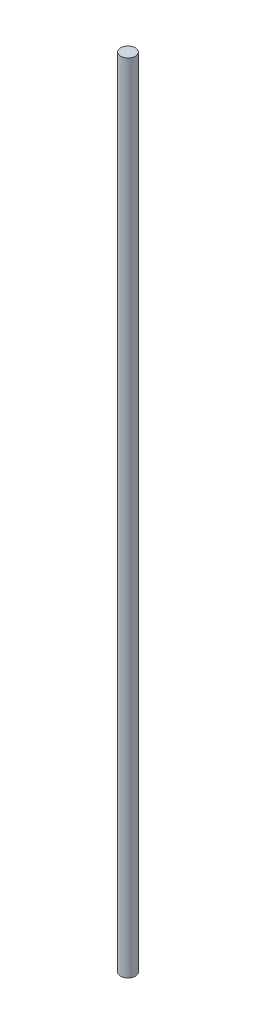
SolidWorks part; units mm, degrees
ref_plane "Plan de face" through (0, 0, 0) normal (0, 0, 1) x (1, 0, 0)
ref_plane "Plan de dessus" through (0, 0, 0) normal (0, 1, 0) x (1, 0, 0)
ref_plane "Plan de droite" through (0, 0, 0) normal (1, 0, 0) x (0, 0, -1)
sketch "Esquisse1" plane through (0, 0, 0) normal (0, 1, 0) x (1, 0, 0)
  circle A0 centre (0, 0) radius 4
  dimension "D1" = 8
extrude "Boss.-Extru.1" add sketch "Esquisse1" along normal up to surface (433.5704 mm away)
